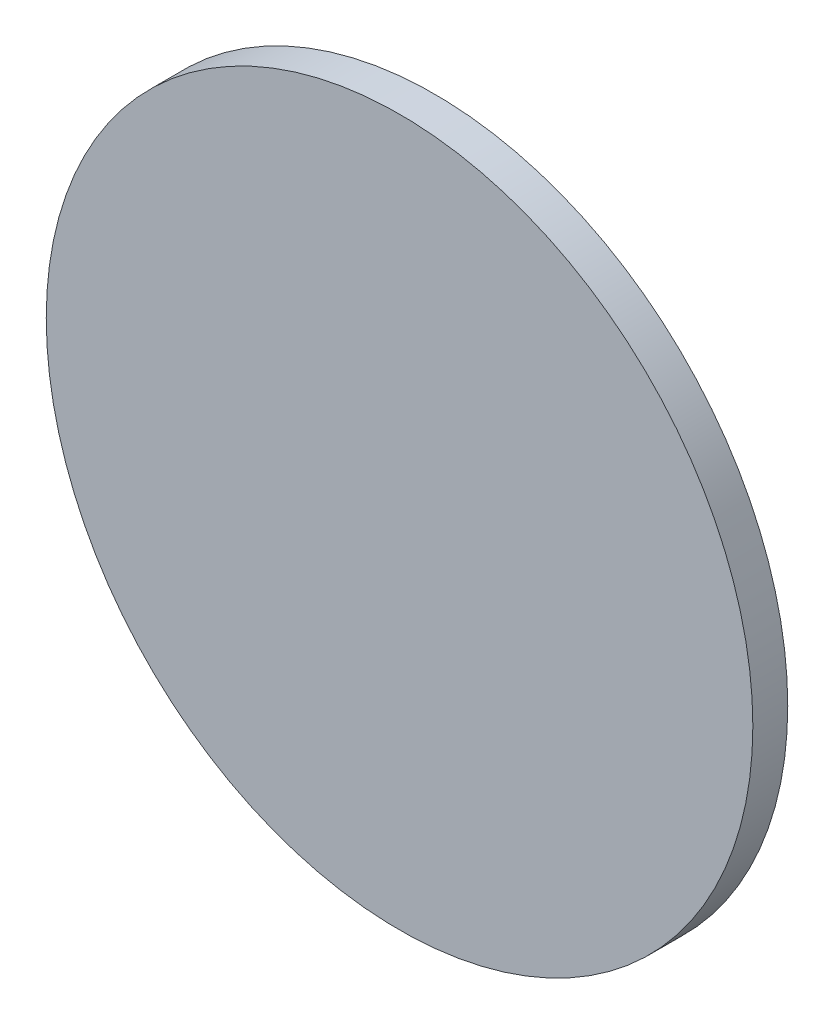
SolidWorks part; units mm, degrees
material "Acrylic (Medium-high impact)"
ref_plane "Front Plane" through (0, 0, 0) normal (0, 0, 1) x (1, 0, 0)
ref_plane "Top Plane" through (0, 0, 0) normal (0, 1, 0) x (1, 0, 0)
ref_plane "Right Plane" through (0, 0, 0) normal (1, 0, 0) x (0, 0, -1)
sketch "Sketch1" plane through (0, 0, 0) normal (0, 0, 1) x (1, 0, 0)
  circle A0 centre (0, 0) radius 16.9672
  dimension "D1" = 33.9344
extrude "Boss-Extrude1" add sketch "Sketch1" along normal blind 1.6764
